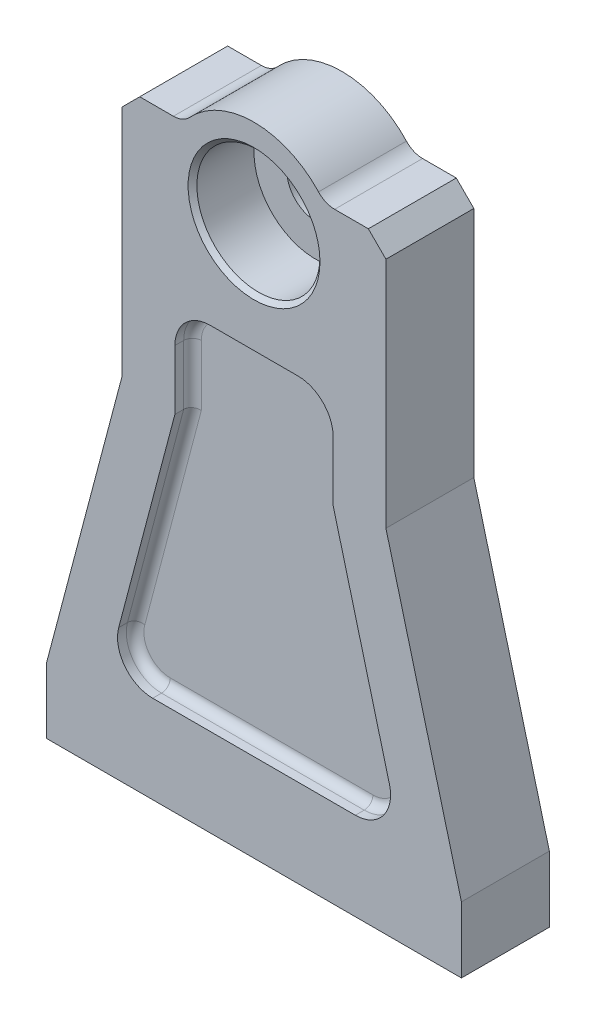
SolidWorks part; units mm, degrees
ref_plane "Front Plane" through (0, 0, 0) normal (0, 0, 1) x (1, 0, 0)
ref_plane "Top Plane" through (0, 0, 0) normal (0, 1, 0) x (1, 0, 0)
ref_plane "Right Plane" through (0, 0, 0) normal (1, 0, 0) x (0, 0, -1)
sketch "Sketch1" plane through (0, 0, 0) normal (0, 0, 1) x (1, 0, 0)
  line L0 (-47.1704, 0) -> (47.1704, 0)
  line L1 (47.1704, 0) -> (47.1704, 15)
  line L2 (47.1704, 15) -> (30, 80)
  line L3 (30, 80) -> (30, 137)
  line L4 (30, 137) -> (16, 137)
  line L5 (0, 0) -> (0, -50000) construction
  line L6 (-47.1704, 0) -> (-47.1704, 15)
  line L7 (-30, 137) -> (-16, 137)
  line L8 (-30, 80) -> (-30, 137)
  line L9 (-47.1704, 15) -> (-30, 80)
  circle A0 centre (0, 125) radius 6.5
  circle A1 centre (0, 125) radius 20
  point P18 (0, 0)
  dimension "D2" = 13
  dimension "D3" = 40
  dimension "D1" = 125
  dimension "D4" = 47.1704
  dimension "D5" = 15
  dimension "D6" = 65
  dimension "D7" = 12
  dimension "D8" = 30
extrude "Boss-Extrude1" add sketch "Sketch1" along normal mid plane 20 contours A1 L5 L0 L1 L2 L3 L4 | L5 A1 L7 L8 L9 L6 L0 | A1 L5 A0 | L5 A1 A0
sketch "Sketch2" plane through (0, 0, 10) normal (0, 0, 1) x (1, 0, 0)
  circle A0 centre (0, 125) radius 14
  dimension "D1" = 28
extrude "Cut-Extrude1" cut sketch "Sketch2" against normal blind 14
chamfer "Chamfer1" distance 4 angle 45 2 edges at (-30, 137, 0) (30, 137, 0)
chamfer "Chamfer2" distance 1 angle 45 1 edges at (14, 125, 10)
fillet "Fillet2" radius 5 2 edges at (-16, 137, 0) (16, 137, 0)
sketch "Sketch3" plane through (0, 0, 10) normal (0, 0, 1) x (1, 0, 0)
  line L3 (-10, 100) -> (10, 100)
  line L4 (18, 78.4418) -> (18, 133)
  line L5 (35.5683, 11.9352) -> (18, 78.4418)
  line L6 (18, 78.4418) -> (18, 92)
  line L7 (30.7849, 30.0432) -> (18, 78.4418)
  line L8 (-47.1704, 20) -> (47.1704, 20)
  line L9 (-23.0503, 20) -> (23.0503, 20)
  line L10 (-47.1704, 0) -> (47.1704, 0) construction
  line L37 (-18, 78.4418) -> (-18, 133)
  line L38 (-35.5683, 11.9352) -> (-18, 78.4418)
  line L39 (-18, 78.4418) -> (-18, 92)
  line L40 (-30.7849, 30.0432) -> (-18, 78.4418)
  arc A0 (-30.7849, 30.0432) -> (-23.0503, 20) centre (-23.0503, 28) ccw
  arc A1 (30.7849, 30.0432) -> (23.0503, 20) centre (23.0503, 28) cw
  arc A2 (18, 92) -> (10, 100) centre (10, 92) ccw
  arc A6 (-18, 92) -> (-10, 100) centre (-10, 92) cw
  dimension "D5" = 8
  dimension "D4" = 100
  dimension "D1" = 12
  dimension "D2" = 12
  dimension "D3" = 20
extrude "Cut-Extrude2" cut sketch "Sketch3" against normal blind 4
fillet "Fillet3" radius 2 10 edges at (-24.3925, 54.2425, 6) (-18, 85.2209, 6) (-15.6569, 97.6569, 6) (0, 100, 6) (15.6569, 97.6569, 6) (18, 85.2209, 6) (24.3925, 54.2425, 6) (29.3885, 23.1187, 6) (0, 20, 6) (-29.3885, 23.1187, 6)
mirror "Mirror1" about plane through (0, 0, 0) normal (0, 0, 1) of "Fillet3", "Cut-Extrude2"
hole_wizard "M10x1.25 Tapped Hole1" positions "Sketch4" profile "Sketch6" tap size "M10x1.25" standard "ISO"
sketch "Sketch4" plane through (0, 0, 0) normal (0, -1, 0) x (-1, 0, 0)
  line L0 (-47.1704, -10) -> (-47.1704, 10) construction
  line L2 (47.1704, -10) -> (-47.1704, -10) construction
  point P0 (-31.1704, 0)
  point P2 (28.8296, 0)
  dimension "D1" = 60
  dimension "D2" = 16
  dimension "D3" = 10
sketch "Sketch6" plane through (31.1704, 0, 0) normal (1, 0, 0) x (0, 0, -1)
  line L0 (0, 0) -> (0, 22.6438)
  line L1 (0, 22.6438) -> (4.4, 20)
  line L2 (4.4, 20) -> (4.4, 0.625)
  line L3 (4.4, 0.625) -> (5.025, 0)
  line L5 (5.025, 0) -> (0, 0)
  line L6 (-4.4, 0.625) -> (-5.025, 0) construction
  line L10 (0, 22.6438) -> (-4.4, 20) construction
  line L11 (0, -6.35) -> (0, 107.95) construction
  dimension "Tap Drill Dia." = 8.8
  dimension "Tap Drill Depth" = 20
  dimension "Near C'Sink Dia." = 10.05
  dimension "Near C'Sink Angle" = 90
  dimension "Drill Angle" = 118
cosmetic thread "Hole Thread1" parameters "D1"=20, "D2"=10
cosmetic thread "Hole Thread2" parameters "D1"=20, "D2"=10
